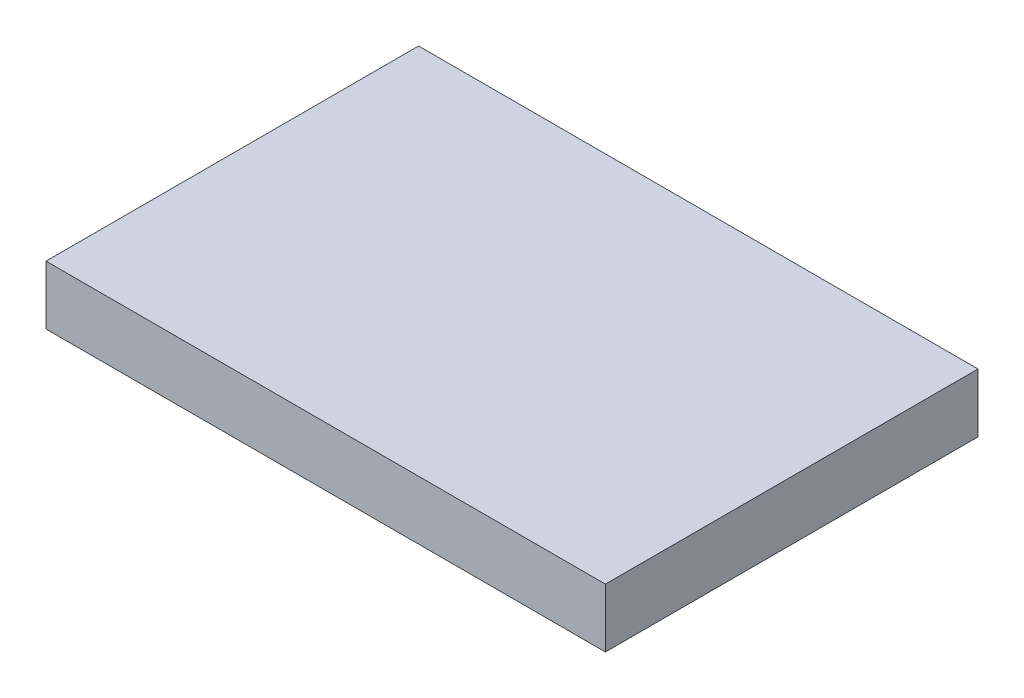
SolidWorks part; units mm, degrees
ref_plane "Front Plane" through (0, 0, 0) normal (0, 0, 1) x (1, 0, 0)
ref_plane "Top Plane" through (0, 0, 0) normal (0, 1, 0) x (1, 0, 0)
ref_plane "Right Plane" through (0, 0, 0) normal (1, 0, 0) x (0, 0, -1)
sketch "Sketch1" plane through (0, 0, 0) normal (0, 1, 0) x (1, 0, 0)
  line L1 (16.6456, -11.0871) -> (-16.6456, -11.0871)
  line L2 (16.6456, -11.0871) -> (16.6456, 11.0871)
  line L3 (16.6456, 11.0871) -> (-16.6456, 11.0871)
  line L4 (-16.6456, -11.0871) -> (-16.6456, 11.0871)
  line L5 (16.6456, -11.0871) -> (-16.6456, 11.0871) construction
  line L6 (16.6456, 11.0871) -> (-16.6456, -11.0871) construction
  point P0 (0, 0)
  dimension "D1" = 40
extrude "Boss-Extrude1" add sketch "Sketch1" along normal blind 3.5
